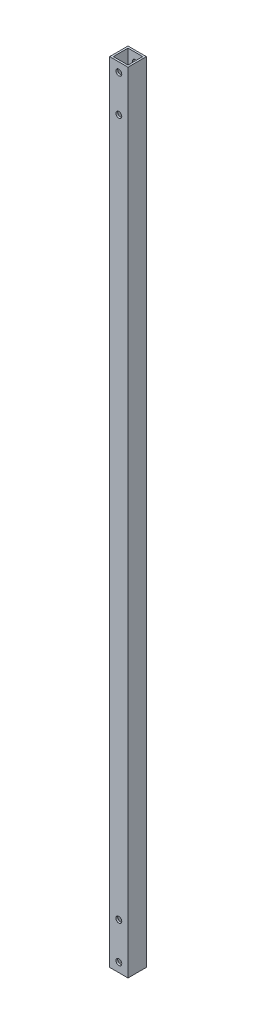
SolidWorks part; units mm, degrees
ref_plane "正面" through (0, 0, 0) normal (0, 0, 1) x (1, 0, 0)
ref_plane "平面" through (0, 0, 0) normal (0, 1, 0) x (1, 0, 0)
ref_plane "右側面" through (0, 0, 0) normal (1, 0, 0) x (0, 0, -1)
sketch "ｽｹｯﾁ1" plane through (0, 0, 0) normal (0, 1, 0) x (1, 0, 0)
  line L0 (-4, 4) -> (4, 4)
  line L1 (-5, 5) -> (5, 5)
  line L2 (-5, 5) -> (-5, -5)
  line L3 (-5, -5) -> (5, -5)
  line L4 (5, 5) -> (5, -5)
  line L5 (-5, 5) -> (5, -5) construction
  line L6 (-5, -5) -> (5, 5) construction
  line L7 (4, 4) -> (4, -4)
  line L8 (-4, -4) -> (4, -4)
  line L9 (-4, 4) -> (-4, -4)
  point P0 (0, 0)
  dimension "D1" = 10
  dimension "D2" = 1
extrude "ﾎﾞｽ - 押し出し1" add sketch "ｽｹｯﾁ1" along normal mid plane 429.94
sketch "ｽｹｯﾁ2" plane through (0, 0, 5) normal (0, 0, 1) x (1, 0, 0)
  line L0 (0, 214.97) -> (0, 209.97) construction
  line L1 (-5, 214.97) -> (5, 214.97) construction
  line L2 (0, 209.97) -> (0, 189.97) construction
  circle A0 centre (0, 209.97) radius 1.6
  circle A1 centre (0, 189.97) radius 1.6
  dimension "D3" = 3.2
  dimension "D4" = 3.2
  dimension "D1" = 5
  dimension "D2" = 20
extrude "ｶｯﾄ - 押し出し1" cut sketch "ｽｹｯﾁ2" against normal mid plane 427.43
mirror "ﾐﾗｰ1" about plane through (0, 0, 0) normal (0, 1, 0) of "ｶｯﾄ - 押し出し1"
